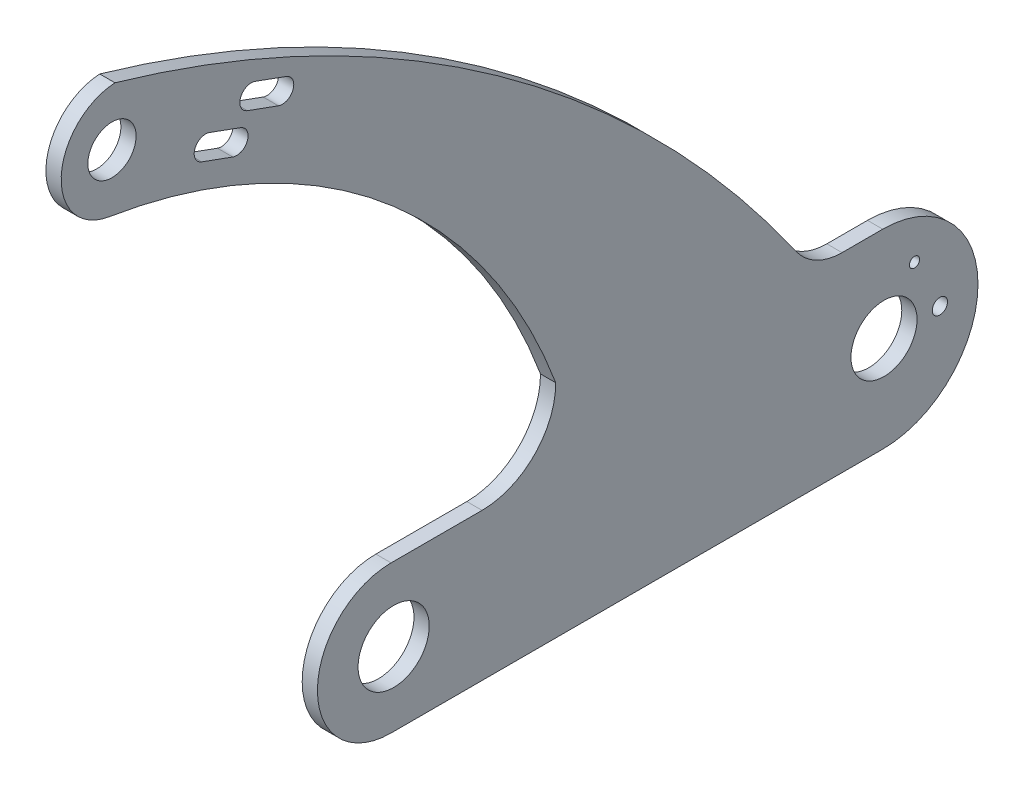
SolidWorks part; units mm, degrees
material "AISI 1020"
ref_plane "Front Plane" through (0, 0, 0) normal (0, 0, 1) x (1, 0, 0)
ref_plane "Top Plane" through (0, 0, 0) normal (0, 1, 0) x (1, 0, 0)
ref_plane "Right Plane" through (0, 0, 0) normal (1, 0, 0) x (0, 0, -1)
sketch "Sketch1" plane through (0, 0, 0) normal (1, 0, 0) x (0, 0, -1)
  line L0 (-48.375, 0) -> (48.375, 0)
  line L1 (48.375, 37.5) -> (40.375, 37.5)
  line L2 (-48.375, 29) -> (-30.475, 29)
  line L3 (0, -31.4761) -> (0, 31.4761) construction
  line L4 (-102.7221, 138) -> (-35.7221, 138) construction
  line L5 (31.3643, 42.1907) -> (-35.7221, 138) construction
  line L6 (46.625, 18.75) -> (48.625, 18.75) construction
  line L7 (46.625, 23.25) -> (48.625, 23.25)
  line L8 (46.625, 14.25) -> (48.625, 14.25)
  line L9 (-102.7221, 138) -> (-103.8892, 115.7306) construction
  line L10 (-103.3056, 126.8653) -> (-113.2919, 127.3886) construction
  line L11 (-15.975, 43.5) -> (-23.475, 56.4904) construction
  line L12 (58.7209, 18.75) -> (60.4234, 18.75) construction
  line L13 (-50.3822, 14.5) -> (-47.4326, 14.5) construction
  line L14 (-49.1942, 14.5) -> (-46.982, 14.5) construction
  line L15 (-84.8817, 118.0957) -> (-78.7737, 115.8726) construction
  line L16 (-84.1122, 120.21) -> (-78.0042, 117.9869)
  line L17 (-85.6513, 115.9814) -> (-79.5433, 113.7583)
  line L18 (-85.8572, 113.2563) -> (-75.7195, 113.2563) construction
  line L19 (-75.8899, 122.3244) -> (-69.7819, 120.1012) construction
  line L20 (-75.1203, 124.4387) -> (-69.0123, 122.2155)
  line L21 (-76.6594, 120.21) -> (-70.5514, 117.9869)
  line L22 (-78.7737, 117.9869) -> (-76.6322, 117.9869) construction
  line L23 (-70.7643, 117.9869) -> (-68.6512, 117.9869) construction
  arc A3 (-48.375, 0) -> (-48.375, 29) centre (-48.375, 14.5) cw
  arc A4 (48.375, 37.5) -> (48.375, 0) centre (48.375, 18.75) cw
  arc A5 (40.375, 37.5) -> (31.3643, 42.1907) centre (40.375, 48.5) cw
  arc A6 (31.3643, 42.1907) -> (-102.7221, 138) centre (-171.3118, -99.7247) ccw
  arc A7 (-15.975, 43.5) -> (-30.475, 29) centre (-30.475, 43.5) cw
  arc A12 (-102.7221, 138) -> (-103.8892, 115.7306) centre (-102.0912, 126.8016) ccw
  arc A13 (-103.8892, 115.7306) -> (-15.975, 43.5) centre (-122.0292, 4.0349) cw
  circle A14 centre (59.625, 18.75) radius 1.5
  arc A15 (46.625, 23.25) -> (46.625, 14.25) centre (46.625, 18.75) ccw
  arc A16 (48.625, 14.25) -> (48.625, 23.25) centre (48.625, 18.75) ccw
  circle A17 centre (54.625, 28.75) radius 1
  circle A18 centre (-47.875, 14.5) radius 7
  circle A19 centre (-103.3056, 126.8653) radius 4.75
  arc A20 (-84.1122, 120.21) -> (-85.6513, 115.9814) centre (-84.8817, 118.0957) ccw
  arc A21 (-79.5433, 113.7583) -> (-78.0042, 117.9869) centre (-78.7737, 115.8726) ccw
  arc A22 (-75.1203, 124.4387) -> (-76.6594, 120.21) centre (-75.8899, 122.3244) ccw
  arc A23 (-70.5514, 117.9869) -> (-69.0123, 122.2155) centre (-69.7819, 120.1012) ccw
  point P2 (-62.875, 14.5)
  point P3 (67.125, 18.75)
  point P5 (0, 0)
  point P14 (0, 0)
  point P26 (47.625, 18.75)
  point P34 (-113.2919, 127.3886)
  point P39 (42.125, 18.75)
  point P40 (53.125, 18.75)
  point P53 (-81.8277, 116.9842)
  point P60 (-86.996, 118.8653)
  point P61 (-76.6594, 115.1031)
  point P64 (-72.8359, 121.2128)
  point P71 (-78.0042, 123.0939)
  point P72 (-67.6676, 119.3317)
  point P77 (-73.6054, 119.0985)
  dimension "D4" = 11
  dimension "D3" = 14.5
  dimension "D1" = 130
  dimension "D2" = 18.75
  dimension "D8" = 14.5
  dimension "D15" = 22.3
  dimension "D17" = 93
  dimension "D18" = 15
  dimension "D11" = 3
  dimension "D16" = 11
  dimension "D21" = 2
  dimension "D24" = 14
  dimension "D26" = 9.5
  dimension "D5" = 8
  dimension "D6" = 125
  dimension "D7" = 138
  dimension "D9" = 67
  dimension "D10" = 32.4
  dimension "D12" = 10
  dimension "D13" = 7.5
  dimension "D14" = 14.5
  dimension "D19" = 9
  dimension "D20" = 14
  dimension "D22" = 12.5
  dimension "D23" = 10
  dimension "D25" = 15
  dimension "D27" = 11
  dimension "D28" = 4.5
  dimension "D29" = 20
  dimension "D30" = 16.3096
  dimension "D31" = 8
  dimension "D32" = 11
  dimension "D33" = 4.5
extrude "Boss-Extrude1" add sketch "Sketch1" along normal blind 3
sketch "Sketch2" plane through (3, 0, 0) normal (1, 0, 0) x (0, 0, -1)
  circle A0 centre (48.625, 18.75) radius 6.5
  dimension "D1" = 13
extrude "Cut-Extrude1" cut sketch "Sketch2" against normal through all both and the other way through all
